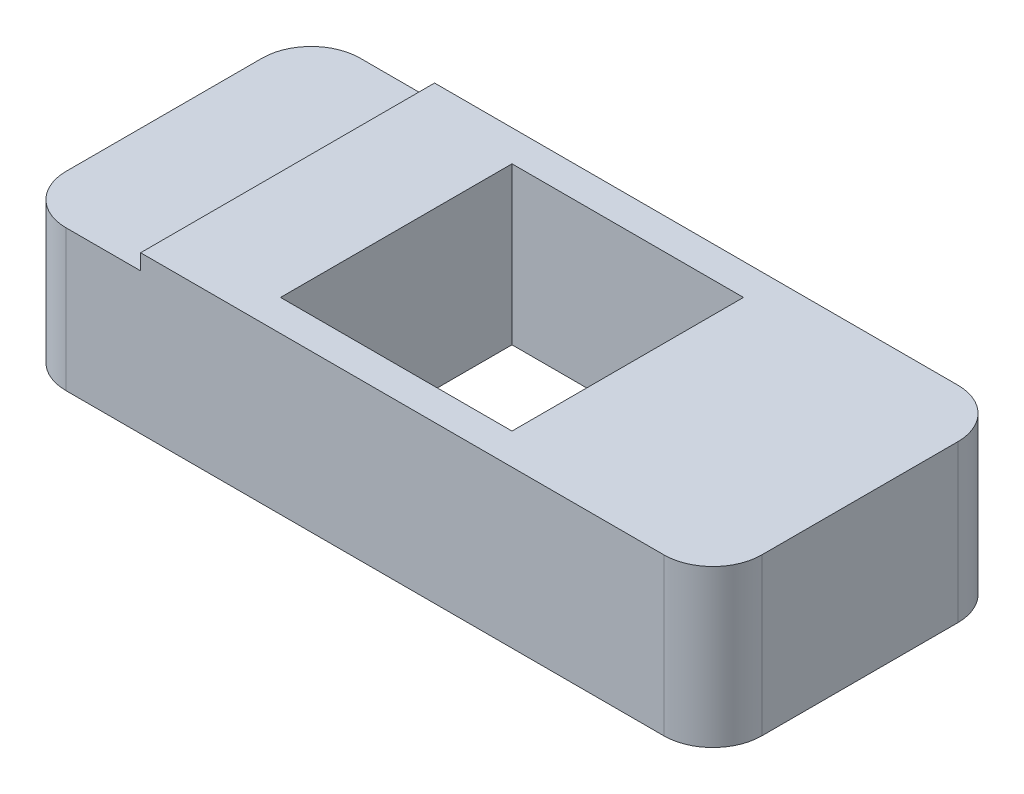
SolidWorks part; units mm, degrees
ref_plane "Front Plane" through (0, 0, 0) normal (0, 0, 1) x (1, 0, 0)
ref_plane "Top Plane" through (0, 0, 0) normal (0, 1, 0) x (1, 0, 0)
ref_plane "Right Plane" through (0, 0, 0) normal (1, 0, 0) x (0, 0, -1)
sketch "Sketch1" plane through (0, 0, 0) normal (0, 1, 0) x (1, 0, 0)
  line L1 (-22.5425, -9.525) -> (22.5425, -9.525)
  line L2 (-22.5425, -9.525) -> (-22.5425, 9.525)
  line L3 (-22.5425, 9.525) -> (22.5425, 9.525)
  line L4 (22.5425, -9.525) -> (22.5425, 9.525)
  line L5 (-22.5425, -9.525) -> (22.5425, 9.525) construction
  line L6 (-22.5425, 9.525) -> (22.5425, -9.525) construction
  point P0 (0, 0)
  dimension "D1" = 19.05
  dimension "D2" = 45.085
extrude "Boss-Extrude1" add sketch "Sketch1" against normal blind 10.16
sketch "Sketch2" plane through (0, 0, 0) normal (0, 1, 0) x (1, 0, 0)
  line L1 (-7.5, -7.5) -> (7.5, -7.5)
  line L2 (-7.5, -7.5) -> (-7.5, 7.5)
  line L3 (-7.5, 7.5) -> (7.5, 7.5)
  line L4 (7.5, -7.5) -> (7.5, 7.5)
  line L5 (-7.5, -7.5) -> (7.5, 7.5) construction
  line L6 (-7.5, 7.5) -> (7.5, -7.5) construction
  point P0 (0, 0)
  dimension "D1" = 15
extrude "Cut-Extrude1" cut sketch "Sketch2" against normal through all
ref_plane "Plane1" through (0, -10, 0) normal (0, 1, 0) x (1, 0, 0)
fillet "Fillet1" radius 3.175 4 edges at (-22.5425, -5.08, 9.525) (-22.5425, -5.08, -9.525) (22.5425, -5.08, 9.525) (22.5425, -5.08, -9.525)
sketch "Sketch3" plane through (0, 0, 0) normal (0, 1, 0) x (1, 0, 0)
  line L0 (-14.5425, -9.525) -> (-14.5425, 9.525)
  line L1 (-19.3675, -9.525) -> (19.3675, -9.525) construction
  line L2 (19.3675, 9.525) -> (-19.3675, 9.525) construction
  line L5 (-22.5425, 6.35) -> (-22.5425, -6.35) construction
  dimension "D1" = 8
extrude "Cut-Extrude2" cut sketch "Sketch3" against normal blind 1.016 and the other way through all
sketch "Sketch5" plane through (0, -10.16, 0) normal (0, -1, 0) x (1, 0, 0)
  line L0 (7.5, 7.5) -> (7.5, -7.5) construction
  line L1 (-21.216, -3.6662) -> (-14.866, -7.3323)
  line L2 (-14.866, -7.3323) -> (-8.516, -3.6662)
  line L3 (-8.516, -3.6662) -> (-8.516, 3.6662)
  line L4 (-8.516, 3.6662) -> (-14.866, 7.3323)
  line L5 (-14.866, 7.3323) -> (-21.216, 3.6662)
  line L6 (-21.216, 3.6662) -> (-21.216, -3.6662)
  line L7 (8.516, -3.6662) -> (14.866, -7.3323)
  line L8 (14.866, -7.3323) -> (21.216, -3.6662)
  line L9 (21.216, -3.6662) -> (21.216, 3.6662)
  line L10 (21.216, 3.6662) -> (14.866, 7.3323)
  line L11 (14.866, 7.3323) -> (8.516, 3.6662)
  line L12 (8.516, 3.6662) -> (8.516, -3.6662)
  line L13 (-7.5, -7.5) -> (-7.5, 7.5) construction
  line L14 (22.5425, 6.35) -> (22.5425, -6.35) construction
  line L15 (-22.5425, -6.35) -> (-22.5425, 6.35) construction
  circle A0 centre (-14.866, 0) radius 6.35 construction
  circle A1 centre (14.866, 0) radius 6.35 construction
  point P26 (7.5, 0)
  point P27 (-8.516, 0)
  dimension "D1" = 12.7
  dimension "D2" = 12.7
  dimension "D3" = 7.366
  dimension "D4" = 7.366
extrude "Cut-Extrude3" cut sketch "Sketch5" against normal blind 8.636
